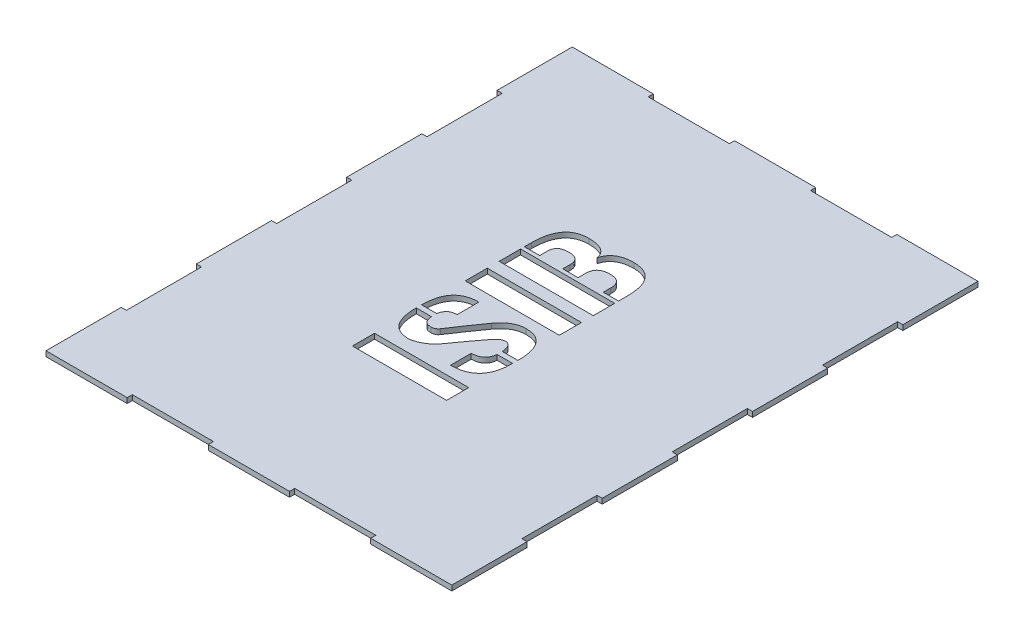
SolidWorks part; units mm, degrees
material "A286 Superalliage à base de fer"
ref_plane "Plan de face" through (0, 0, 0) normal (0, 0, 1) x (1, 0, 0)
ref_plane "Plan de dessus" through (0, 0, 0) normal (0, 1, 0) x (1, 0, 0)
ref_plane "Plan de droite" through (0, 0, 0) normal (1, 0, 0) x (0, 0, -1)
sketch "Esquisse1" plane through (0, 0, 0) normal (0, 1, 0) x (1, 0, 0)
  line L0 (-115, -150) -> (115, 150) construction
  line L1 (-70.8, 150) -> (-23.6, 150)
  line L2 (-115, 109.2857) -> (-115, 65.5714)
  line L3 (-70.8, -150) -> (-23.6, -150)
  line L4 (115, 109.2857) -> (115, 65.5714)
  line L5 (-118, 153) -> (-70.8, 153)
  line L6 (118, 153) -> (118, 109.2857)
  line L7 (-118, -153) -> (-70.8, -153)
  line L8 (-118, 153) -> (-118, 109.2857)
  line L9 (-70.8, 153) -> (-70.8, 150)
  line L10 (-23.6, 153) -> (-23.6, 150)
  line L11 (23.6, 153) -> (23.6, 150)
  line L12 (-70.8, -153) -> (-70.8, -150)
  line L13 (-23.6, 153) -> (23.6, 153)
  line L14 (70.8, 153) -> (70.8, 150)
  line L15 (-118, 153) -> (118, 153) construction
  line L16 (70.8, 153) -> (118, 153)
  line L17 (23.6, 150) -> (70.8, 150)
  line L18 (-23.6, -150) -> (-23.6, -153)
  line L19 (-115, 150) -> (115, 150) construction
  line L20 (23.6, -150) -> (23.6, -153)
  line L21 (70.8, -150) -> (70.8, -153)
  line L22 (23.6, -150) -> (70.8, -150)
  line L23 (-115, -150) -> (115, -150) construction
  line L24 (70.8, -153) -> (118, -153)
  line L25 (-23.6, -153) -> (23.6, -153)
  line L26 (-118, -153) -> (118, -153) construction
  line L27 (118, 109.2857) -> (115, 109.2857)
  line L28 (-118, 21.8571) -> (-115, 21.8571)
  line L29 (118, -21.8571) -> (115, -21.8571)
  line L30 (-118, -65.5714) -> (-115, -65.5714)
  line L31 (118, -109.2857) -> (115, -109.2857)
  line L32 (-118, 65.5714) -> (-115, 65.5714)
  line L33 (115, 65.5714) -> (118, 65.5714)
  line L34 (115, 21.8571) -> (118, 21.8571)
  line L35 (-115, -21.8571) -> (-118, -21.8571)
  line L36 (115, -65.5714) -> (118, -65.5714)
  line L37 (-115, -109.2857) -> (-118, -109.2857)
  line L38 (-115, 109.2857) -> (-118, 109.2857)
  line L39 (-118, 65.5714) -> (-118, 21.8571)
  line L40 (-115, 150) -> (-115, -150) construction
  line L41 (-115, 21.8571) -> (-115, -21.8571)
  line L42 (-118, 153) -> (-118, -153) construction
  line L43 (-118, -21.8571) -> (-118, -65.5714)
  line L44 (-115, -65.5714) -> (-115, -109.2857)
  line L45 (-118, -109.2857) -> (-118, -153)
  line L46 (118, -109.2857) -> (118, -153)
  line L47 (115, 150) -> (115, -150) construction
  line L48 (115, -65.5714) -> (115, -109.2857)
  line L49 (118, 153) -> (118, -153) construction
  line L50 (118, -21.8571) -> (118, -65.5714)
  line L51 (115, 21.8571) -> (115, -21.8571)
  line L52 (118, 65.5714) -> (118, 21.8571)
  point P38 (-115, -87.4286)
  dimension "D1" = 300
  dimension "D2" = 230
  dimension "D3" = 3
extrude "Boss.-Extru.1" add sketch "Esquisse1" along normal blind 3
sketch "Esquisse3" plane through (0, 3, 0) normal (0, -1, 0) x (1, 0, 0)
  line L0 (23.4533, -153) -> (23.4533, 153) construction
  text T0 "ISIB" font "Gunplay" height in points 200
extrude "Enlèv. mat.-Extru.4" cut sketch "Esquisse3" along normal up to surface (3 mm away) up to face at (0, 0, 0)
